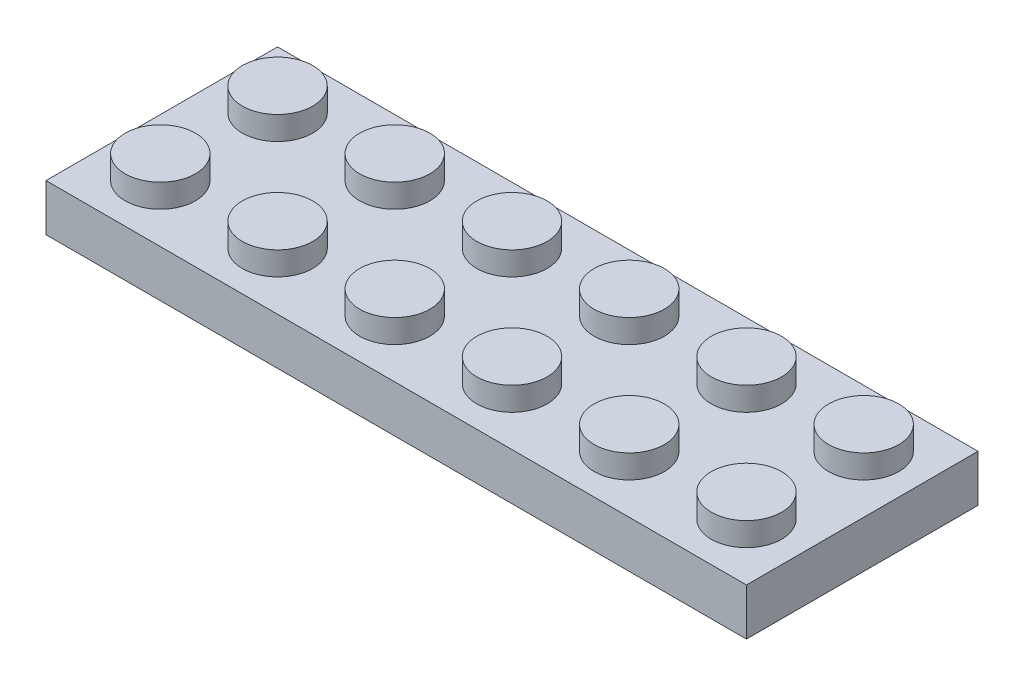
SolidWorks part; units mm, degrees
material "ABS"
ref_plane "Front Plane" through (0, 0, 0) normal (0, 0, 1) x (1, 0, 0)
ref_plane "Top Plane" through (0, 0, 0) normal (0, 1, 0) x (1, 0, 0)
ref_plane "Right Plane" through (0, 0, 0) normal (1, 0, 0) x (0, 0, -1)
sketch "Sketch1" plane through (0, 0, 0) normal (0, 0, 1) x (1, 0, 0)
  line L1 (0, 0) -> (47.8, 0)
  line L2 (0, 0) -> (0, 3.2)
  line L3 (0, 3.2) -> (47.8, 3.2)
  line L4 (47.8, 0) -> (47.8, 3.2)
  dimension "D1" = 3.2
  dimension "D2" = 47.8
extrude "Boss-Extrude1" add sketch "Sketch1" against normal blind 15.8
sketch "Sketch2" plane through (0, 3.2, 0) normal (0, 1, 0) x (1, 0, 0)
  line L0 (0, 15.8) -> (0, 0) construction
  line L1 (47.8, 0) -> (0, 0) construction
  circle A0 centre (3.9, 3.9) radius 2.4
  dimension "D1" = 4.8
  dimension "D2" = 3.9
  dimension "D3" = 3.9
extrude "Boss-Extrude2" add sketch "Sketch2" along normal blind 1.6 contours A0
pattern_linear "LPattern1" count 2 spacing 8 along (0, 0, -1) count 6 spacing 8 along (1, 0, 0) of "Boss-Extrude2"
shell "Shell1" thickness 1.2
sketch "Sketch3" plane through (0, 2, 0) normal (0, -1, 0) x (1, 0, 0)
  line L0 (0, -15.8) -> (0, 0) construction
  line L1 (0, -15.8) -> (47.8, -15.8) construction
  circle A0 centre (7.9, -7.9) radius 3.25
  circle A1 centre (7.9, -7.9) radius 2.4
  dimension "D1" = 4.8
  dimension "D2" = 6.5
  dimension "D3" = 7.9
  dimension "D4" = 7.9
extrude "Boss-Extrude3" add sketch "Sketch3" along normal offset from surface (1.8 mm away) 0.2 up to face at (23.9, 0, -7.9)
pattern_linear "LPattern2" count 5 spacing 8 along (1, 0, 0) of "Boss-Extrude3"
